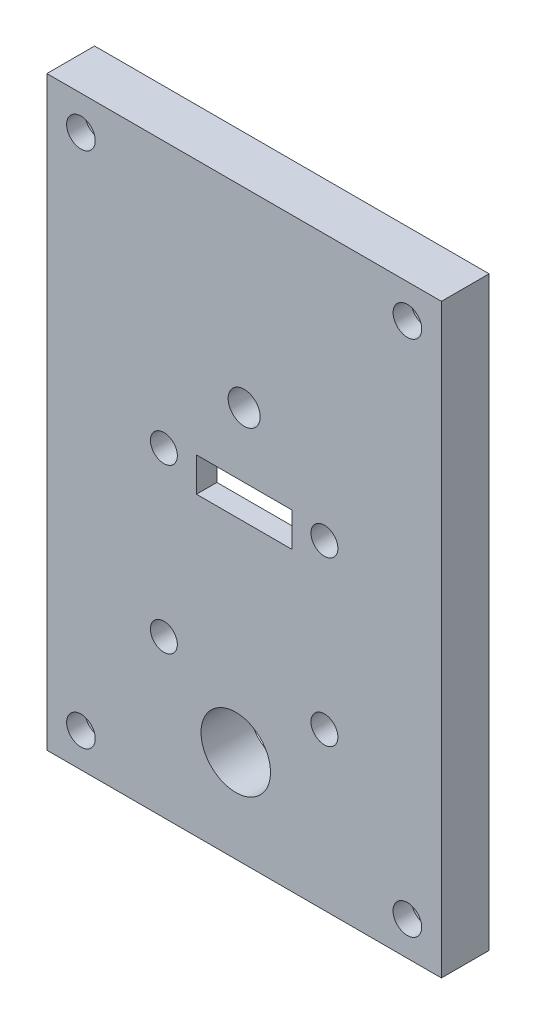
SolidWorks part; units mm, degrees
ref_plane "Plan de face" through (0, 0, 0) normal (0, 0, 1) x (1, 0, 0)
ref_plane "Plan de dessus" through (0, 0, 0) normal (0, 1, 0) x (1, 0, 0)
ref_plane "Plan de droite" through (0, 0, 0) normal (1, 0, 0) x (0, 0, -1)
sketch "Esquisse1" plane through (0, 0, 0) normal (0, 0, 1) x (1, 0, 0)
  line L1 (-28.95, 43) -> (28.95, 43)
  line L2 (-28.95, 43) -> (-28.95, -43)
  line L3 (-28.95, -43) -> (28.95, -43)
  line L4 (28.95, 43) -> (28.95, -43)
  line L5 (-28.95, 43) -> (28.95, -43) construction
  line L6 (-28.95, -43) -> (28.95, 43) construction
  point P0 (0, 0)
  dimension "D1" = 57.9
  dimension "D2" = 86
extrude "Boss.-Extru.1" add sketch "Esquisse1" along normal blind 7
sketch "Esquisse3" plane through (0, 0, 0) normal (0, 0, -1) x (-1, 0, 0)
  line L0 (28.95, 43) -> (28.95, -43) construction
  line L1 (-23.95, 38) -> (-23.9604, 38.0198) construction
  line L2 (-23.95, 38) -> (-23.9604, 38) construction
  line L3 (28.95, -43) -> (-28.95, -43) construction
  line L4 (-28.95, -43) -> (-28.95, 43) construction
  line L6 (-23.9604, 38.0198) -> (-23.9604, 38) construction
  line L7 (-28.95, 43) -> (28.95, 43) construction
  circle A0 centre (23.95, 38) radius 2.1
  circle A1 centre (-23.9604, 38.0198) radius 2.1
  circle A2 centre (23.95, -38) radius 2.1
  circle A3 centre (-23.95, -38) radius 2.1
  circle A4 centre (1.2293, -29.4111) radius 5.1
  dimension "D1" = 4.2
  dimension "D2" = 4.2
  dimension "D3" = 4.2
  dimension "D4" = 4.2
  dimension "D5" = 10.2
  dimension "D6" = 5
  dimension "D7" = 5
  dimension "D8" = 5
  dimension "D9" = 5
  dimension "D10" = 5
  dimension "D11" = 5
  dimension "D12" = 5
  dimension "D13" = 5
extrude "Enlèv. mat.-Extru.2" cut sketch "Esquisse3" against normal through all
sketch "Esquisse4" plane through (0, 0, 0) normal (0, 0, -1) x (-1, 0, 0)
  circle A0 centre (23.95, -38) radius 3.75
  circle A1 centre (-23.95, -38) radius 3.75
  circle A2 centre (23.95, 38) radius 3.75
  dimension "D1" = 7.5
  dimension "D3" = 7.5
  dimension "D4" = 7.5
extrude "Enlèv. mat.-Extru.3" cut sketch "Esquisse4" against normal blind 4.3
sketch "Esquisse6" plane through (0, 0, 0) normal (0, 0, -1) x (-1, 0, 0)
  line L0 (-28.95, -43) -> (-28.95, 43) construction
  line L1 (-28.95, 43) -> (28.95, 43) construction
  circle A0 centre (-23.95, 38) radius 3.75
  dimension "D1" = 7.5
  dimension "D2" = 5
  dimension "D3" = 5
extrude "Enlèv. mat.-Extru.5" cut sketch "Esquisse6" against normal blind 4.3 contours A0
sketch "Esquisse7" plane through (0, 0, 0) normal (0, 0, -1) x (-1, 0, 0)
  line L0 (0, 0) -> (0, -8) construction
  line L2 (14, 6.5) -> (-14, 6.5)
  line L3 (14, 6.5) -> (14, -22.5)
  line L4 (14, -22.5) -> (-14, -22.5)
  line L5 (-14, 6.5) -> (-14, -22.5)
  line L6 (14, 6.5) -> (-14, -22.5) construction
  line L7 (14, -22.5) -> (-14, 6.5) construction
  point P4 (0, -8)
  dimension "D1" = 8
  dimension "D2" = 28
  dimension "D3" = 29
extrude "Enlèv. mat.-Extru.6" cut sketch "Esquisse7" against normal blind 4
sketch "Esquisse9" plane through (0, 0, 4) normal (0, 0, -1) x (-1, 0, 0)
  line L0 (14, -22.5) -> (-14, 6.5) construction
  line L1 (0, -19.99) -> (0, 3.01) construction
  line L2 (11.78, -19.99) -> (-11.78, -19.99) construction
  line L3 (11.78, -19.99) -> (11.78, 3.99) construction
  line L4 (11.78, 3.99) -> (-11.78, 3.99) construction
  line L5 (-11.78, -19.99) -> (-11.78, 3.99) construction
  line L6 (11.78, -19.99) -> (-11.78, 3.99) construction
  line L7 (11.78, 3.99) -> (-11.78, -19.99) construction
  line L8 (7, 5.51) -> (-7, 5.51)
  line L9 (7, 5.51) -> (7, 0.51)
  line L10 (7, 0.51) -> (-7, 0.51)
  line L11 (-7, 5.51) -> (-7, 0.51)
  line L12 (7, 5.51) -> (-7, 0.51) construction
  line L13 (7, 0.51) -> (-7, 5.51) construction
  circle A0 centre (11.78, -19.99) radius 1.975
  circle A1 centre (-11.78, -19.99) radius 1.975
  circle A2 centre (-11.78, 3.99) radius 1.975
  circle A3 centre (11.78, 3.99) radius 1.975
  point P2 (0, -8)
  point P18 (0, 3.01)
  dimension "D3" = 3.95
  dimension "D1" = 23.56
  dimension "D2" = 23.98
  dimension "D4" = 14
  dimension "D5" = 5
  dimension "D6" = 23
extrude "Enlèv. mat.-Extru.7" cut sketch "Esquisse9" against normal through all
sketch "Esquisse10" plane through (0, 0, 0) normal (0, 0, -1) x (-1, 0, 0)
  line L0 (0, 15) -> (0, 0) construction
  circle A0 centre (0, 15) radius 2.35
  dimension "D2" = 4.7
  dimension "D1" = 15
extrude "Enlèv. mat.-Extru.8" cut sketch "Esquisse10" against normal through all
